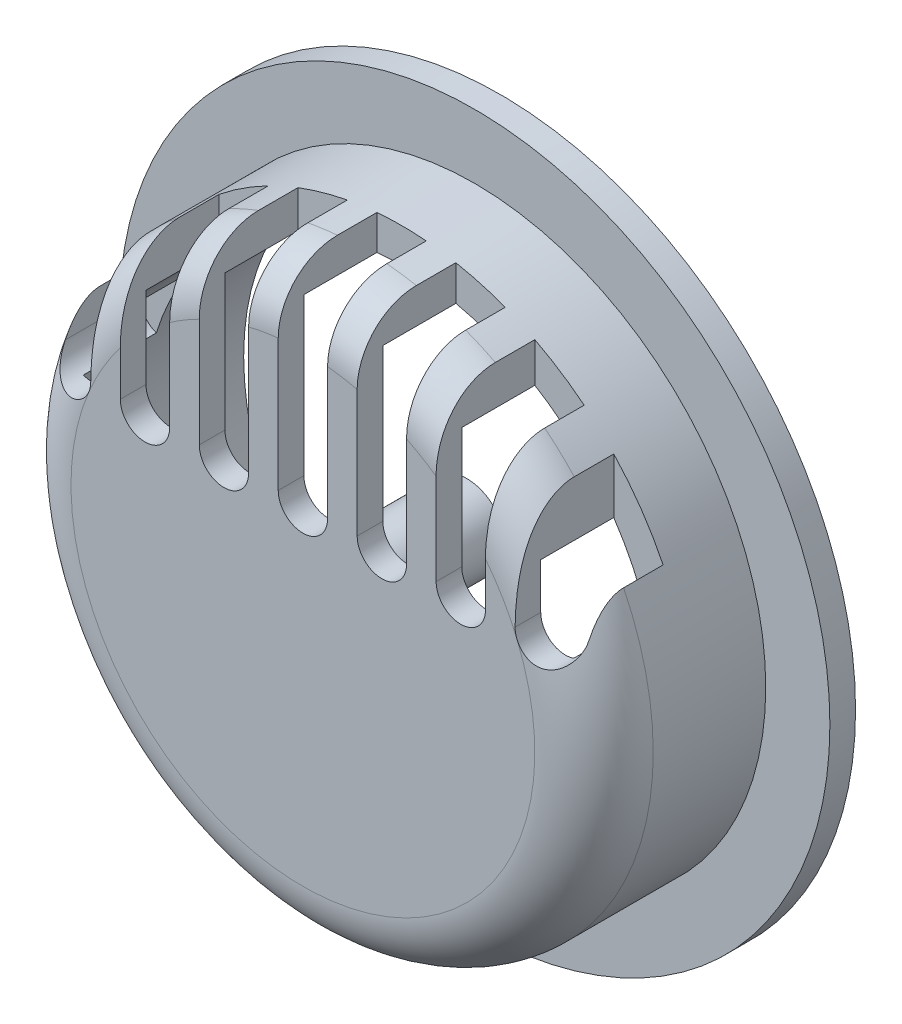
SolidWorks part; units mm, degrees
ref_plane "Front Plane" through (0, 0, 0) normal (0, 0, 1) x (1, 0, 0)
ref_plane "Top Plane" through (0, 0, 0) normal (0, 1, 0) x (1, 0, 0)
ref_plane "Right Plane" through (0, 0, 0) normal (1, 0, 0) x (0, 0, -1)
sketch "Sketch1" plane through (0, 0, 0) normal (0, 0, 1) x (1, 0, 0)
  circle A0 centre (0, 0) radius 18
  dimension "D1" = 36
extrude "Boss-Extrude1" add sketch "Sketch1" along normal blind 1.3
sketch "Sketch2" plane through (0, 0, 1.3) normal (0, 0, 1) x (1, 0, 0)
  circle A0 centre (0, 0) radius 14.75
  dimension "D1" = 29.5
extrude "Boss-Extrude2" add sketch "Sketch2" along normal blind 8.7
fillet "Fillet1" radius 3 1 edges at (14.75, 0, 10)
sketch "Sketch3" plane through (0, 0, 0) normal (0, 0, -1) x (-1, 0, 0)
  circle A0 centre (0, 0) radius 13
  dimension "D1" = 26
extrude "Cut-Extrude1" cut sketch "Sketch3" against normal blind 8.7
sketch "Sketch4" plane through (0, 0, 8.7) normal (0, 0, -1) x (-1, 0, 0)
  circle A0 centre (0, 0) radius 2
  dimension "D1" = 4
extrude "Boss-Extrude3" add sketch "Sketch4" along normal blind 7
sketch "Sketch5" plane through (0, 0, 1.7) normal (0, 0, -1) x (-1, 0, 0)
  circle A0 centre (0, 0) radius 1.15
  dimension "D1" = 2.3
extrude "Cut-Extrude2" cut sketch "Sketch5" against normal blind 6
sketch "Sketch8" plane through (0, 0, 10) normal (0, 0, 1) x (1, 0, 0)
  line L0 (0, 5) -> (0, 20) construction
  line L1 (-1.25, 5) -> (-1.25, 20)
  line L2 (1.25, 5) -> (1.25, 20)
  line L3 (4, 5) -> (4, 20) construction
  line L4 (2.75, 5) -> (2.75, 20)
  line L5 (5.25, 5) -> (5.25, 20)
  line L6 (8, 5) -> (8, 20) construction
  line L7 (6.75, 5) -> (6.75, 20)
  line L8 (9.25, 5) -> (9.25, 20)
  line L9 (12, 5) -> (12, 20) construction
  line L10 (10.75, 5) -> (10.75, 20)
  line L11 (13.25, 5) -> (13.25, 20)
  line L12 (0, 5) -> (4, 5) construction
  line L13 (-4, 5) -> (-4, 20) construction
  line L14 (-5.25, 5) -> (-5.25, 20)
  line L15 (-2.75, 5) -> (-2.75, 20)
  line L16 (-8, 5) -> (-8, 20) construction
  line L17 (-9.25, 5) -> (-9.25, 20)
  line L18 (-6.75, 5) -> (-6.75, 20)
  line L19 (-12, 5) -> (-12, 20) construction
  line L20 (-13.25, 5) -> (-13.25, 20)
  line L21 (-10.75, 5) -> (-10.75, 20)
  line L22 (0, 5) -> (-4, 5) construction
  arc A0 (-1.25, 5) -> (1.25, 5) centre (0, 5) ccw
  arc A1 (1.25, 20) -> (-1.25, 20) centre (0, 20) ccw
  arc A2 (2.75, 5) -> (5.25, 5) centre (4, 5) ccw
  arc A3 (5.25, 20) -> (2.75, 20) centre (4, 20) ccw
  arc A4 (6.75, 5) -> (9.25, 5) centre (8, 5) ccw
  arc A5 (9.25, 20) -> (6.75, 20) centre (8, 20) ccw
  arc A6 (10.75, 5) -> (13.25, 5) centre (12, 5) ccw
  arc A7 (13.25, 20) -> (10.75, 20) centre (12, 20) ccw
  arc A8 (-5.25, 5) -> (-2.75, 5) centre (-4, 5) ccw
  arc A9 (-2.75, 20) -> (-5.25, 20) centre (-4, 20) ccw
  arc A10 (-9.25, 5) -> (-6.75, 5) centre (-8, 5) ccw
  arc A11 (-6.75, 20) -> (-9.25, 20) centre (-8, 20) ccw
  arc A12 (-13.25, 5) -> (-10.75, 5) centre (-12, 5) ccw
  arc A13 (-10.75, 20) -> (-13.25, 20) centre (-12, 20) ccw
  point P3 (0, 12.5)
  point P12 (4, 12.5)
  point P19 (8, 12.5)
  point P26 (12, 12.5)
  point P34 (-4, 12.5)
  point P41 (-8, 12.5)
  point P48 (-12, 12.5)
  dimension "D1" = 2.5
  dimension "D2" = 15
  dimension "D3" = 5
  dimension "D5" = 4
  dimension "D7" = 4
  dimension "D4" = 4
  dimension "D6" = 4
extrude "Cut-Extrude3" cut sketch "Sketch8" against normal blind 5
